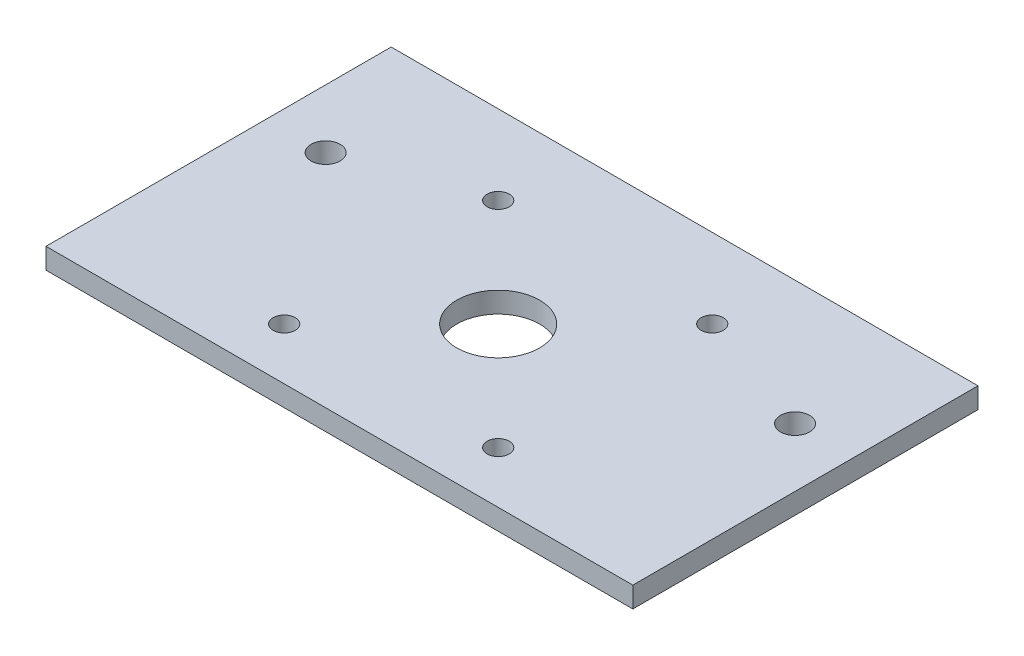
SolidWorks part; units mm, degrees
ref_plane "Front Plane" through (0, 0, 0) normal (0, 0, 1) x (1, 0, 0)
ref_plane "Top Plane" through (0, 0, 0) normal (0, 1, 0) x (1, 0, 0)
ref_plane "Right Plane" through (0, 0, 0) normal (1, 0, 0) x (0, 0, -1)
sketch "Sketch1" plane through (0, 0, 0) normal (0, 1, 0) x (1, 0, 0)
  line L1 (-65, 45) -> (65, 45)
  line L2 (-65, 45) -> (-65, -45)
  line L3 (-65, -45) -> (65, -45)
  line L4 (65, 45) -> (65, -45)
  line L5 (-65, 45) -> (65, -45) construction
  line L6 (-65, -45) -> (65, 45) construction
  point P0 (0, 0)
  dimension "D1" = 130
  dimension "D2" = 90
extrude "Boss-Extrude1" add sketch "Sketch1" along normal blind 3
sketch "Sketch2" plane through (0, 3, 0) normal (0, 1, 0) x (1, 0, 0)
  line L0 (81.2168, 18) -> (-62.8548, 18) construction
  line L1 (65, 45) -> (-65, 45) construction
  line L2 (0, 0) -> (0, -27.9829) construction
  circle A0 centre (15.5, 2.5) radius 1.6
  circle A1 centre (-15.5, 2.5) radius 1.6
  circle A2 centre (-15.5, 33.5) radius 1.6
  circle A3 centre (15.5, 33.5) radius 1.6
  dimension "D3" = 15.5
  dimension "D4" = 15.5
  dimension "D5" = 15.5
  dimension "D6" = 15.5
  dimension "D7" = 15.5
  dimension "D8" = 15.5
  dimension "D9" = 15.5
  dimension "D10" = 15.5
  dimension "D11" = 3.2
  dimension "D2" = 27
extrude "Cut-Extrude1" cut sketch "Sketch2" against normal blind 10
sketch "Sketch3" plane through (0, 0, 0) normal (0, -1, 0) x (1, 0, 0)
  line L1 (65, -45) -> (-65, -45) construction
  circle A2 centre (-34, -27) radius 2.1
  circle A3 centre (34, -27) radius 2.1
  dimension "D1" = 34
  dimension "D2" = 34
  dimension "D3" = 18
  dimension "D6" = 4.2
extrude "Cut-Extrude2" cut sketch "Sketch3" against normal blind 10
sketch "Sketch4" plane through (0, 0, 0) normal (0, -1, 0) x (1, 0, 0)
  circle A0 centre (0, -18) radius 6
  circle A2 centre (-15.5, -33.5) radius 1.6 construction
  dimension "D1" = 12
  dimension "D2" = 15.5
  dimension "D3" = 15.5
extrude "Cut-Extrude3" cut sketch "Sketch4" against normal blind 10
sketch "Sketch5" plane through (0, 3, 0) normal (0, 1, 0) x (1, 0, 0)
  line L0 (-65, 45) -> (-65, -45) construction
  line L1 (-42.5, 45) -> (42.5, 45)
  line L2 (-42.5, 45) -> (-42.5, -5)
  line L3 (-42.5, -5) -> (42.5, -5)
  line L4 (42.5, 45) -> (42.5, -5)
  line L5 (65, 45) -> (-65, 45) construction
  line L7 (-105.4522, 62.4257) -> (106.4471, 62.4257)
  line L8 (-105.4522, 62.4257) -> (-105.4522, -75.6073)
  line L9 (-105.4522, -75.6073) -> (106.4471, -75.6073)
  line L10 (106.4471, 62.4257) -> (106.4471, -75.6073)
  dimension "D1" = 85
  dimension "D2" = 22.5
  dimension "D3" = 0
  dimension "D4" = 50
extrude "Cut-Extrude4" cut sketch "Sketch5" against normal blind 10
